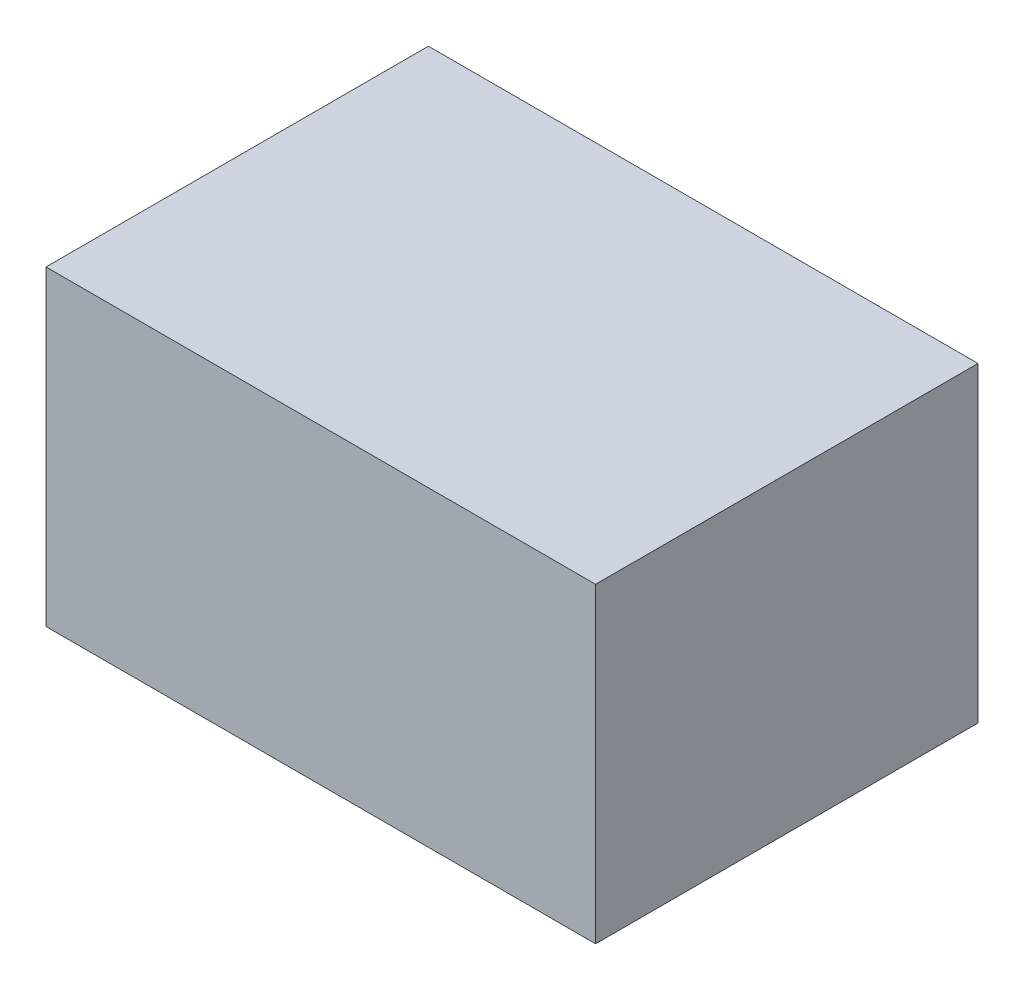
SolidWorks part; units mm, degrees
ref_plane "Ebene vorne" through (0, 0, 0) normal (0, 0, 1) x (1, 0, 0)
ref_plane "Ebene oben" through (0, 0, 0) normal (0, 1, 0) x (1, 0, 0)
ref_plane "Ebene rechts" through (0, 0, 0) normal (1, 0, 0) x (0, 0, -1)
sketch "Skizze1" plane through (0, 0, 0) normal (0, 0, 1) x (1, 0, 0)
  line L1 (0, 0) -> (503, 0)
  line L2 (0, 0) -> (0, 285)
  line L3 (0, 285) -> (503, 285)
  line L4 (503, 0) -> (503, 285)
  dimension "D1" = 503
  dimension "D2" = 285
extrude "Aufsatz-Linear austragen1" add sketch "Skizze1" along normal blind 350
sketch "Skizze2" plane through (0, 0, 0) normal (0, -1, 0) x (1, 0, 0)
  circle A0 centre (84.3996, 294.5556) radius 19
  circle A1 centre (403.7471, 294.5556) radius 19
  circle A2 centre (403.7471, 75.4712) radius 19
  circle A3 centre (84.3996, 75.4712) radius 19
  point P8 (403.7471, 294.5556)
  point P9 (84.3996, 294.5556)
  dimension "D1" = 38
extrude "Aufsatz-Linear austragen2" add sketch "Skizze2" along normal blind 25
